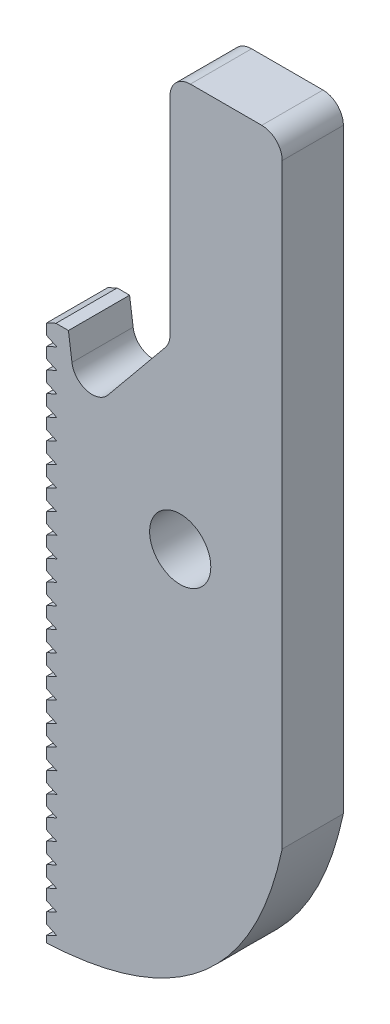
SolidWorks part; units mm, degrees
ref_plane "前视基准面" through (0, 0, 0) normal (0, 0, 1) x (1, 0, 0)
ref_plane "上视基准面" through (0, 0, 0) normal (0, 1, 0) x (1, 0, 0)
ref_plane "右视基准面" through (0, 0, 0) normal (1, 0, 0) x (0, 0, -1)
sketch "草图1" plane through (0, 0, 0) normal (0, 0, 1) x (1, 0, 0)
  line L1 (-5, 20) -> (5, 20)
  line L2 (-5, 20) -> (-5, -20)
  line L3 (-5, -20) -> (5, -20)
  line L4 (5, 20) -> (5, -20)
  line L5 (-5, 20) -> (5, -20) construction
  line L6 (-5, -20) -> (5, 20) construction
  circle A0 centre (0, 0) radius 1.5
  point P0 (0, 0)
  dimension "D1" = 3
  dimension "D2" = 10
  dimension "D3" = 40
extrude "凸台-拉伸1" add sketch "草图1" along normal blind 3
sketch "草图2" plane through (0, 0, 3) normal (0, 0, 1) x (1, 0, 0)
  line L0 (-5, -20) -> (5, -20) construction
  line L1 (-5, 20) -> (-6.55, 20)
  line L2 (-5, 20) -> (-5, -20)
  line L3 (-5, -20) -> (-6.55, -20)
  line L4 (-6.55, 20) -> (-6.55, -20)
  dimension "D1" = 1.55
extrude "凸台-拉伸2" add sketch "草图2" against normal blind 3
sketch "草图3" plane through (0, 0, 3) normal (0, 0, 1) x (1, 0, 0)
  line L0 (-6.05, 20) -> (-6.05, -20) construction
  line L1 (5, 20) -> (-6.55, 20) construction
  line L3 (-6.55, -20) -> (5, -20) construction
  line L4 (-6.55, 20) -> (-6.55, -20) construction
  line L5 (-6.55, 19.8) -> (-6.05, 19.5668)
  line L6 (-6.05, 19.5668) -> (-6.55, 19.3337)
  line L7 (-6.05, 19.5668) -> (-6.55, 19.5668) construction
  line L8 (-6.55, 19.8) -> (-6.55, 19.3337)
  dimension "D1" = 0.5
  dimension "D2" = 50
  dimension "D3" = 0.2
extrude "切除-拉伸1" cut sketch "草图3" against normal blind 3
pattern_linear "阵列(线性)1" count 40 spacing 1 along (0, -1, 0) of "切除-拉伸1"
sketch "草图5" plane through (0, 0, 3) normal (0, 0, 1) x (1, 0, 0)
  line L0 (-0.5, 20) -> (-0.5, 8.4853)
  line L2 (-0.5, 8.4853) -> (-0.5, 42.8063) construction
  line L3 (5, 20) -> (-6.55, 20) construction
  line L4 (-0.5, 8.4853) -> (-5, 3)
  line L5 (-5, 3) -> (-5.4805, 6.5474)
  line L7 (-7.0401, 9.4456) -> (-8.1844, 20)
  line L8 (-8.1844, 20) -> (-0.5, 20)
  line L9 (-5.4805, 6.5474) -> (-7.0401, 6.5474)
  line L10 (-7.0401, 6.5474) -> (-7.0401, 9.4456)
extrude "切除-拉伸2" cut sketch "草图5" against normal blind 10
fillet "圆角1" radius 1 2 edges at (-5, 3, 1.5) (-0.5, 8.4853, 1.5)
sketch "草图7" plane through (0, 0, 0) normal (0, 0, -1) x (-1, 0, 0)
  line L0 (-5, -20) -> (-5, 20) construction
  line L1 (6.55, -20) -> (-5.4182, -22.5669)
  line L2 (-5.4182, -22.5669) -> (-10.0629, -14.0758)
  line L3 (-10.0629, -14.0758) -> (-5, -10.2301)
  spline S0 degree 2 poles (-5, -10.2301) (-3.0258, -19.5548) (6.55, -20) knots 0 0 0 1 1 1
extrude "切除-拉伸3" cut sketch "草图7" against normal blind 10
fillet "圆角2" radius 1 2 edges at (-0.5, 20, 1.5) (5, 20, 1.5)
